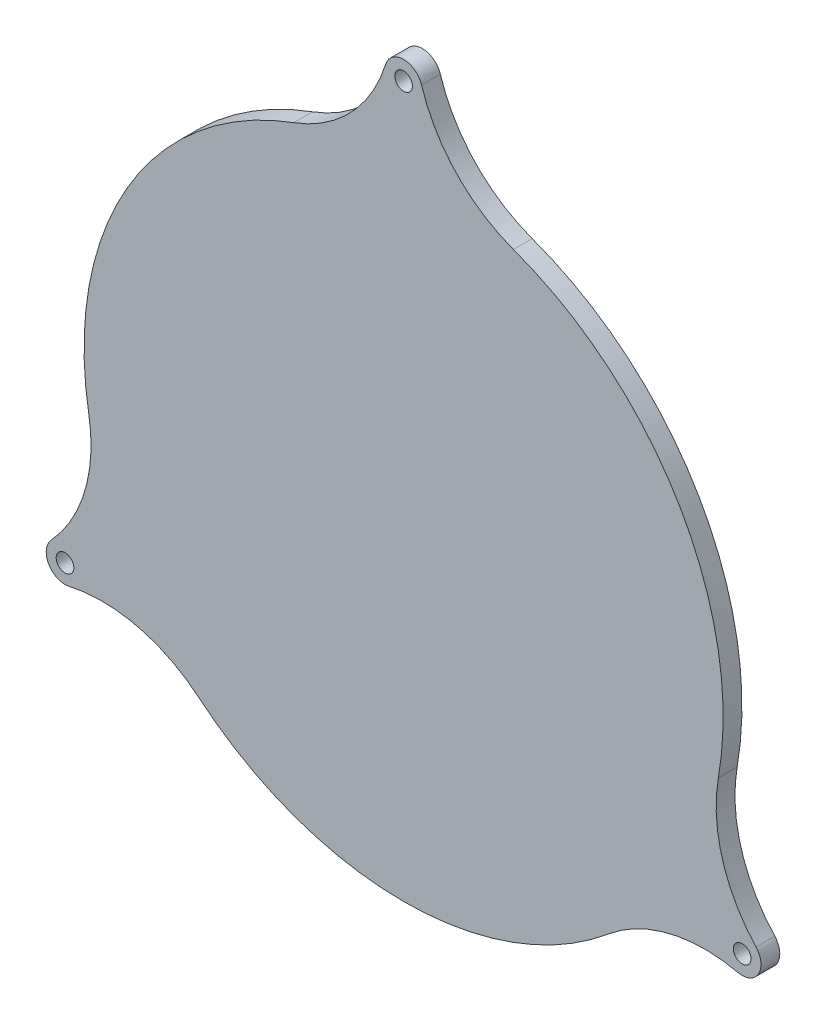
SolidWorks part; units mm, degrees
material "6061-T6 Black anodised"
ref_plane "Front Plane" through (0, 0, 0) normal (0, 0, 1) x (1, 0, 0)
ref_plane "Top Plane" through (0, 0, 0) normal (0, 1, 0) x (1, 0, 0)
ref_plane "Right Plane" through (0, 0, 0) normal (1, 0, 0) x (0, 0, -1)
sketch "Sketch1" plane through (0, 0, 0) normal (0, 0, 1) x (1, 0, 0)
  arc A0 (-29.2151, 79.8215) -> (-83.735, -14.6098) centre (0, 0) ccw
  circle A1 centre (0, 104) radius 2.35
  arc A2 (4.7737, 105.4872) -> (-4.7737, 105.4872) centre (0, 104) ccw
  arc A3 (4.7737, 105.4872) -> (29.2151, 79.8215) centre (42.9634, 117.3846) ccw
  arc A4 (-4.7737, 105.4872) -> (-29.2151, 79.8215) centre (-42.9634, 117.3846) cw
  arc A5 (93.7414, -48.6094) -> (83.735, -14.6098) centre (123.1397, -21.4849) cw
  arc A6 (88.9677, -56.8777) -> (54.5199, -65.2118) centre (80.1764, -95.8997) ccw
  circle A7 centre (90.0666, -52) radius 2.35
  arc A8 (88.9677, -56.8777) -> (93.7414, -48.6094) centre (90.0666, -52) ccw
  arc A9 (-88.9677, -56.8777) -> (-54.5199, -65.2118) centre (-80.1764, -95.8997) cw
  arc A10 (-93.7414, -48.6094) -> (-83.735, -14.6098) centre (-123.1397, -21.4849) ccw
  circle A11 centre (-90.0666, -52) radius 2.35
  arc A12 (-93.7414, -48.6094) -> (-88.9677, -56.8777) centre (-90.0666, -52) ccw
  arc A13 (83.735, -14.6098) -> (29.2151, 79.8215) centre (0, 0) ccw
  arc A14 (-54.5199, -65.2118) -> (54.5199, -65.2118) centre (0, 0) ccw
  circle A15 centre (0, 92) radius 1.6 construction
  circle A16 centre (79.6743, -46) radius 1.6 construction
  circle A17 centre (-79.6743, -46) radius 1.6 construction
  point P29 (0, 0)
  point P36 (0, 0)
  dimension "D1" = 170
  dimension "D3" = 4.7
  dimension "D4" = 5
  dimension "D5" = 40
  dimension "D8" = 3.2
  dimension "D2" = 104
  dimension "D7" = 92
  dimension "D6" = 3
  dimension "D9" = 3
extrude "Boss-Extrude1" add sketch "Sketch1" along normal blind 5
sketch "Sketch2" plane through (0, 0, 5) normal (0, 0, 1) x (1, 0, 0)
  line L0 (0, 75) -> (64.9519, -37.5) construction
  line L1 (64.9519, -37.5) -> (-64.9519, -37.5) construction
  line L2 (-64.9519, -37.5) -> (0, 75) construction
  line L3 (64.9519, -37.5) -> (0, 0) construction
  line L4 (-64.9519, -37.5) -> (0, 0) construction
  line L5 (0, 75) -> (0, -75) construction
  line L6 (-32.476, 18.75) -> (-64.9519, 37.5) construction
  line L7 (32.476, 18.75) -> (64.9519, 37.5) construction
  line L9 (-37.5, 64.9519) -> (-75, 0)
  line L10 (-75, 0) -> (-37.5, -64.9519)
  line L11 (-37.5, -64.9519) -> (37.5, -64.9519)
  line L12 (37.5, -64.9519) -> (75, 0)
  line L13 (75, 0) -> (37.5, 64.9519)
  line L14 (37.5, 64.9519) -> (-37.5, 64.9519)
  circle A0 centre (0, 0) radius 75 construction
  circle A1 centre (0, 0) radius 75 construction
  point P0 (0, 75)
  point P6 (64.9519, -37.5)
  point P7 (-64.9519, -37.5)
  point P8 (0, 0)
  point P10 (-32.476, 18.75)
  point P11 (32.476, 18.75)
  point P12 (0, -37.5)
  point P18 (32.476, -18.75)
  point P19 (-32.476, -18.75)
  dimension "D1" = 150
  dimension "D3" = 120
  dimension "D4" = 120
  dimension "D5" = 64.9519
  dimension "D6" = 18.75
  dimension "D7" = 32.476
  dimension "D8" = 18.75
  dimension "D9" = 32.476
  dimension "D10" = 37.5
  dimension "D11" = 37.5
  dimension "D12" = 64.9519
  dimension "D13" = 37.5
  dimension "D14" = 75
  dimension "D2" = 3
